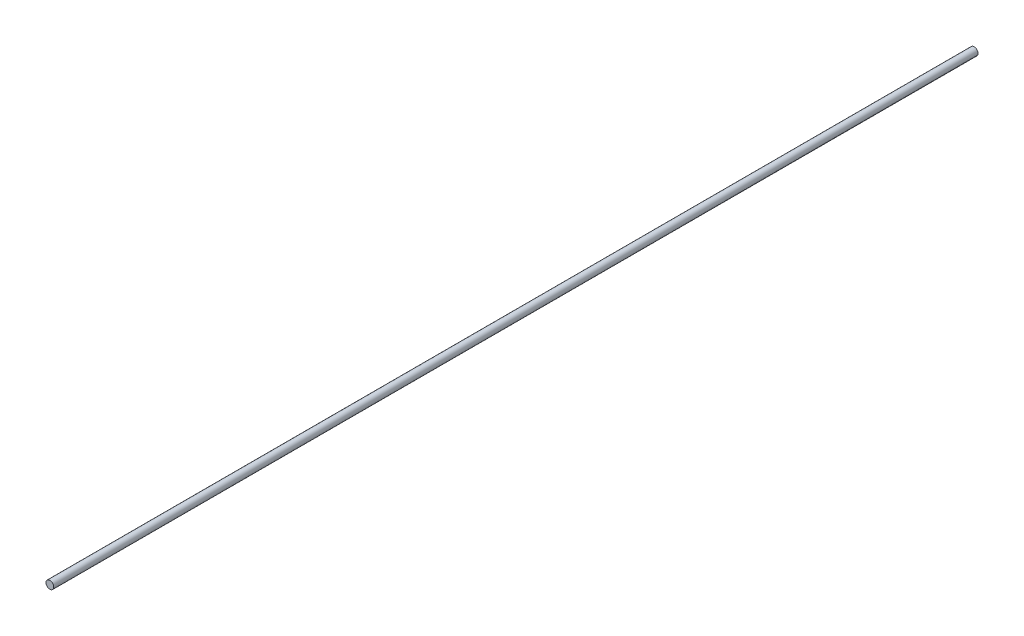
SolidWorks part; units mm, degrees
ref_plane "Plan de face" through (0, 0, 0) normal (0, 0, 1) x (1, 0, 0)
ref_plane "Plan de dessus" through (0, 0, 0) normal (0, 1, 0) x (1, 0, 0)
ref_plane "Plan de droite" through (0, 0, 0) normal (1, 0, 0) x (0, 0, -1)
sketch "Esquisse1" plane through (0, 0, 0) normal (0, 0, 1) x (1, 0, 0)
  circle A0 centre (0, 0) radius 3
extrude "Boss.-Extru.1" add sketch "Esquisse1" along normal blind 715
